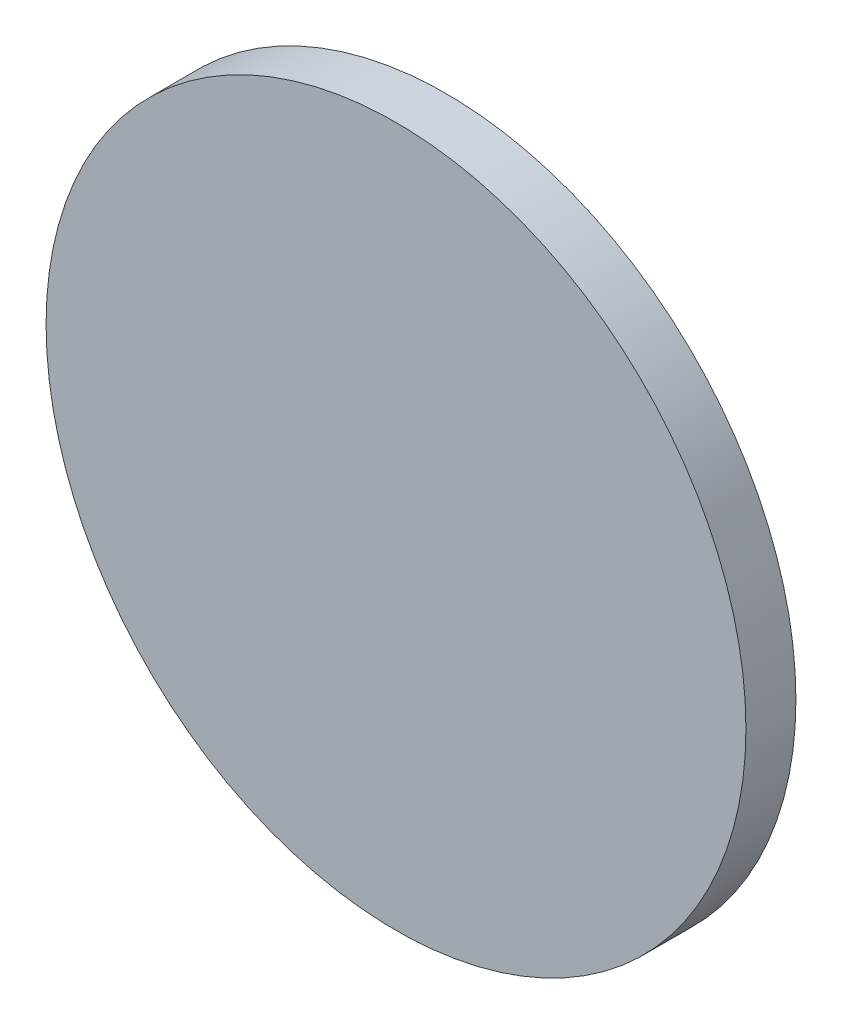
SolidWorks part; units mm, degrees
ref_plane "Front Plane" through (0, 0, 0) normal (0, 0, 1) x (1, 0, 0)
ref_plane "Top Plane" through (0, 0, 0) normal (0, 1, 0) x (1, 0, 0)
ref_plane "Right Plane" through (0, 0, 0) normal (1, 0, 0) x (0, 0, -1)
sketch "Sketch2" plane through (0, 0, 0) normal (0, 0, 1) x (1, 0, 0)
  circle A0 centre (0, 0) radius 70
  dimension "D1" = 140
sketch "Sketch1" plane through (0, 0, 0) normal (0, 0, 1) x (1, 0, 0)
  line L8 (44.8105, 35.7485) -> (-44.8105, 35.7485)
  line L9 (-44.8105, 35.7485) -> (-44.8105, -35.7485)
  line L10 (-44.8105, -35.7485) -> (44.8105, -35.7485)
  line L11 (44.8105, -35.7485) -> (44.8105, 35.7485)
  line L12 (44.8105, 35.7485) -> (-44.8105, 35.7485)
  line L13 (-44.8105, 35.7485) -> (-44.8105, -35.7485)
  line L14 (-44.8105, -35.7485) -> (44.8105, -35.7485)
  line L15 (44.8105, -35.7485) -> (44.8105, 35.7485)
  dimension "D2" = 2.75
extrude "Boss-Extrude1" add sketch "Sketch2" along normal blind 10
extrude "Cut-Extrude1" cut sketch "Sketch1" along normal blind 5
